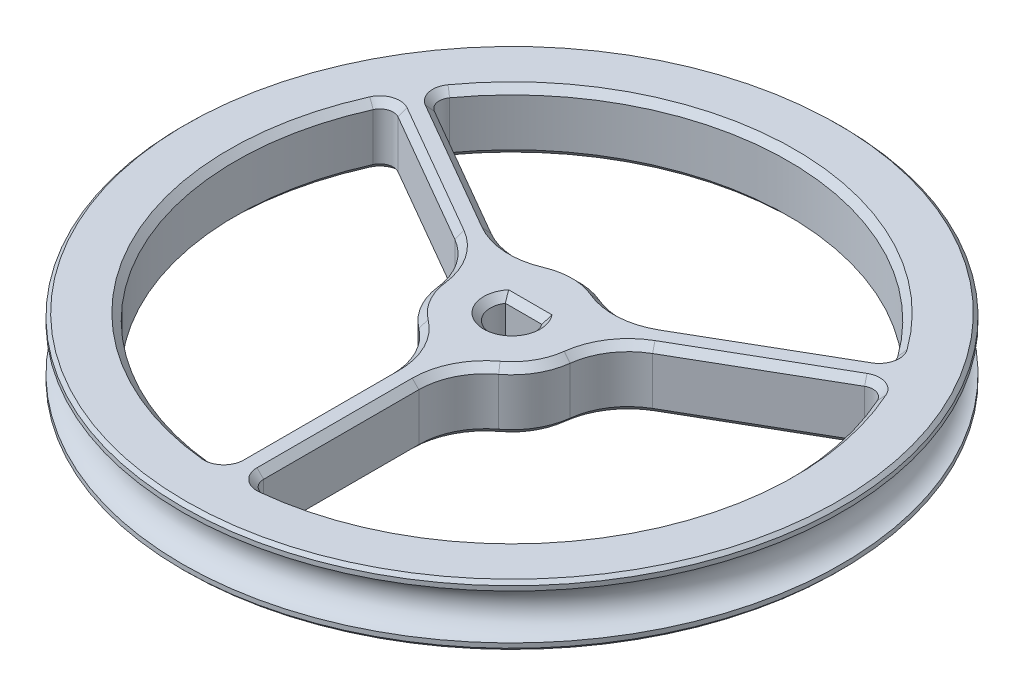
SolidWorks part; units mm, degrees
ref_plane "Front" through (0, 0, 0) normal (0, 0, 1) x (1, 0, 0)
ref_plane "Top" through (0, 0, 0) normal (0, 1, 0) x (1, 0, 0)
ref_plane "Right" through (0, 0, 0) normal (1, 0, 0) x (0, 0, -1)
sketch "Sketch1" plane through (0, 0, 0) normal (0, 1, 0) x (1, 0, 0)
  circle A0 centre (0, 0) radius 24.765
  dimension "D1" = 49.53
extrude "Boss-Extrude1" add sketch "Sketch1" along normal blind 4.572
sketch "Sketch2" plane through (0, 0, 0) normal (1, 0, 0) x (0, 0, -1)
  line L0 (0, 0) -> (0, 4.572) construction
  line L1 (24.765, 4.572) -> (-24.765, 4.572) construction
  line L2 (0, 2.286) -> (25.065, 2.286) construction
  line L3 (24.765, 0) -> (24.765, 4.572) construction
  circle A0 centre (25.065, 2.286) radius 1.7145
  dimension "D1" = 3.429
  dimension "D2" = 0.3
revolve "Cut-Revolve1" cut sketch "Sketch2" angle 360 about L0
sketch "Sketch3" plane through (0, 4.572, 0) normal (0, 1, 0) x (1, 0, 0)
  line L0 (1.365, 0.8854) -> (1.373, 0.873)
  line L1 (1.373, 0.873) -> (-1.373, 0.873)
  arc A0 (-1.373, 0.873) -> (1.373, 0.873) centre (0, 0) ccw
  dimension "D2" = 3.254
  dimension "D1" = 2.5
extrude "Cut-Extrude1" cut sketch "Sketch3" against normal through all contours L1 A0
sketch "Sketch4" plane through (0, 4.572, 0) normal (0, 1, 0) x (1, 0, 0)
  line L0 (0, 0) -> (21.4471, 12.3825) construction
  line L1 (0, 0) -> (0, 24.765) construction
  line L2 (0, 0) -> (-21.4471, 12.3825) construction
  line L3 (3.7426, 3.3155) -> (17.4622, 11.2365)
  line L4 (-3.7426, 3.3155) -> (-17.4622, 11.2365)
  circle A0 centre (0, 0) radius 24.765 construction
  arc A1 (-3.7426, 3.3155) -> (3.7426, 3.3155) centre (0, 0) cw
  arc A3 (-17.4622, 11.2365) -> (17.4622, 11.2365) centre (0, 0) cw
  dimension "D2" = 4
  dimension "D3" = 5
  dimension "D1" = 120
  dimension "D4" = 2
extrude "Cut-Extrude2" cut sketch "Sketch4" against normal through all
pattern_circular "CirPattern1" count 3 every 120 about axis through (0, 0, 0) along (0, 1, 0) of "Cut-Extrude2"
fillet "Fillet1" radius 5 6 edges at (3.7426, 2.286, -3.3155) (-3.7426, 2.286, -3.3155) (4.7426, 2.286, -1.5835) (1, 2.286, 4.899) (-1, 2.286, 4.899) (-4.7426, 2.286, -1.5835)
fillet "Fillet4" radius 1 6 edges at (17.4622, 2.286, -11.2365) (18.4622, 2.286, -9.5044) (-18.4622, 2.286, -9.5044) (-17.4622, 2.286, -11.2365) (1, 2.286, 20.7409) (-1, 2.286, 20.7409)
chamfer "Chamfer1" distance 0.5 angle 45 4 edges at (0, 0, 1.627) (0, 0, -0.873) (0, 4.572, 1.627) (0, 4.572, -0.873)
chamfer "Chamfer2" distance 0.5 angle 45 48 edges at (-1, 0, 13.8318) (-4.3301, 0, 2.5) (-12.4787, 0, -6.0499) (-17.983, 0, 10.3825) (-11.4787, 0, -7.7819) (0, 0, -5) (0, 0, -20.765) (11.4787, 0, -7.7819) (17.983, 0, 10.3825) (12.4787, 0, -6.0499) (4.3301, 0, 2.5) (1, 0, 13.8318) (17.983, 4.572, 10.3825) (1, 4.572, 13.8318) (4.3301, 4.572, 2.5) (12.4787, 4.572, -6.0499) (0, 4.572, -20.765) (11.4787, 4.572, -7.7819) (0, 4.572, -5) (-11.4787, 4.572, -7.7819) (-17.983, 4.572, 10.3825) (-1, 4.572, 13.8318) (-4.3301, 4.572, 2.5) (-12.4787, 4.572, -6.0499) (-5.7556, 0, -1.5588) (-1.5279, 0, 5.7639) (-18.3366, 0, -9.0513) (-1.3296, 0, 20.4056) (-4.2278, 0, -4.2051) (-17.0069, 0, -11.3543) (4.2278, 0, -4.2051) (17.0069, 0, -11.3543) (5.7556, 0, -1.5588) (18.3366, 0, -9.0513) (1.5279, 0, 5.7639) (1.3296, 0, 20.4056) (1.3296, 4.572, 20.4056) (1.5279, 4.572, 5.7639) (18.3366, 4.572, -9.0513) (5.7556, 4.572, -1.5588) (17.0069, 4.572, -11.3543) (4.2278, 4.572, -4.2051) (-17.0069, 4.572, -11.3543) (-4.2278, 4.572, -4.2051) (-1.5279, 4.572, 5.7639) (-1.3296, 4.572, 20.4056) (-5.7556, 4.572, -1.5588) (-18.3366, 4.572, -9.0513)
chamfer "Chamfer3" distance 0.25 angle 45 2 edges at (0, 0, 24.765) (0, 4.572, 24.765)
